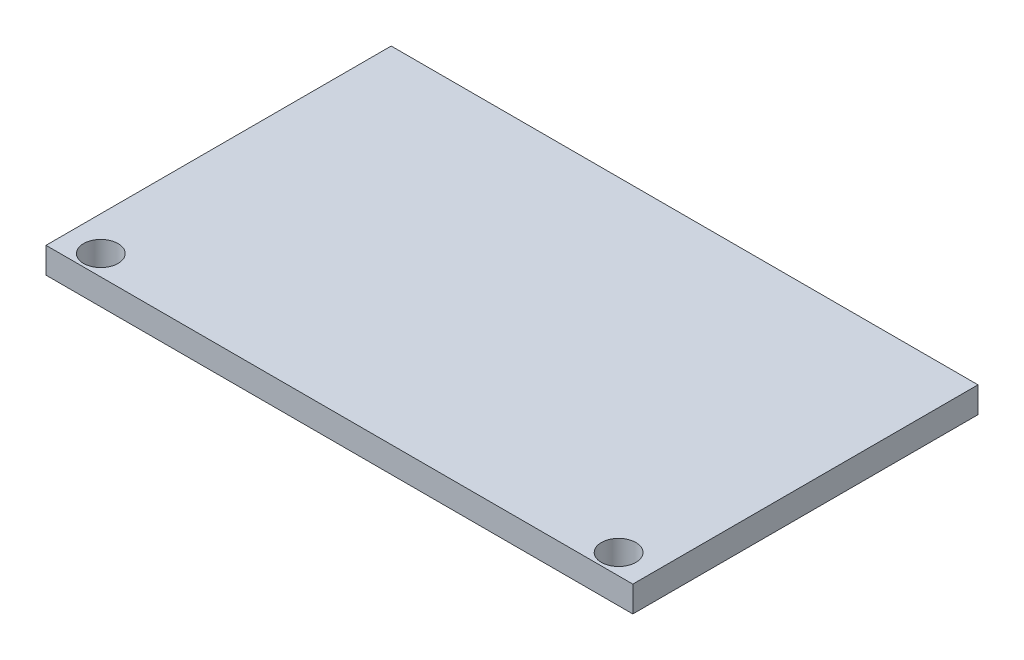
SolidWorks part; units mm, degrees
ref_plane "Front Plane" through (0, 0, 0) normal (0, 0, 1) x (1, 0, 0)
ref_plane "Top Plane" through (0, 0, 0) normal (0, 1, 0) x (1, 0, 0)
ref_plane "Right Plane" through (0, 0, 0) normal (1, 0, 0) x (0, 0, -1)
sketch "Sketch2" plane through (0, 0, 0) normal (0, 1, 0) x (1, 0, 0)
  line L1 (-17, 10) -> (17, 10)
  line L2 (-17, 10) -> (-17, -10)
  line L3 (-17, -10) -> (17, -10)
  line L4 (17, 10) -> (17, -10)
  line L5 (-17, 10) -> (17, -10) construction
  line L6 (-17, -10) -> (17, 10) construction
  circle A0 centre (-15, -8.8235) radius 1
  circle A1 centre (15, -8.8235) radius 1
  point P0 (0, 0)
  dimension "D1" = 34
  dimension "D3" = 2
  dimension "D4" = 2
  dimension "D2" = 20
  dimension "D5" = 30
extrude "Boss-Extrude1" add sketch "Sketch2" along normal blind 1.5
